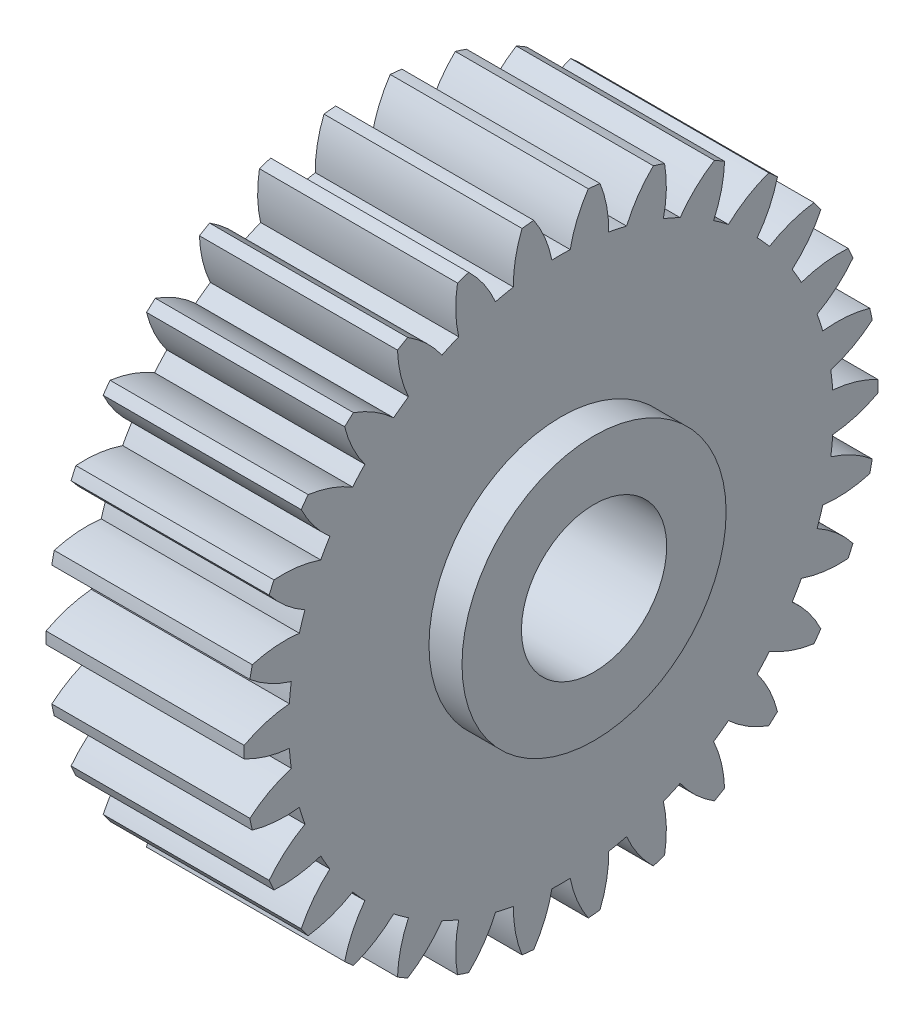
SolidWorks part; units mm, degrees
ref_plane "Plane1" through (0, 0, 0) normal (0, 0, 1) x (1, 0, 0)
ref_plane "Plane2" through (0, 0, 0) normal (0, 1, 0) x (1, 0, 0)
ref_plane "Plane3" through (0, 0, 0) normal (1, 0, 0) x (0, 0, -1)
other "Configuration Table"
sketch "HoldingSke" plane through (0, 0, 0) normal (0, 1, 0) x (1, 0, 0)
  line L0 (0, 0) -> (0.2887, -0.1667)
  line L1 (-15, 0) -> (100, 0) construction
  line L2 (0, 0) -> (-2.1039, 2.3779)
  line L3 (0, 0) -> (-11.863, 4.5341)
  line L4 (0, 0) -> (7.479, 4.318)
  line L5 (0, 0) -> (-37.4781, -13.9782)
  line L6 (0, 0) -> (-24.8689, -16.7791)
  line L7 (-2.1039, 2.3779) -> (6.5061, 41.4403)
  line L8 (-76.2, 54.61) -> (-72.9, 54.61)
  line L9 (-71.009, 38.7566) -> (-53.1078, 45.2721)
  line L10 (-76.2, 71.12) -> (104.1128, 71.12)
  line L11 (0, 0) -> (-30, 0)
  line L12 (-76.2, 101.6) -> (-76.093, 101.6)
  line L13 (24.9733, 27.94) -> (52.9518, 28.4284)
  line L14 (24.9733, 27.94) -> (24.9743, 27.94)
  line L15 (24.9733, 27.94) -> (100.4006, 29.5858)
  line L16 (-63.627, -3) -> (-12.827, -3)
  circle A0 centre (0, 0) radius 11
  circle A1 centre (0, 0) radius 20
  circle A2 centre (0, 0) radius 20
  circle A3 centre (0, 0) radius 11
  dimension "MHD" = 40
  dimension "Hub_dia" = 40
  dimension "Bore" = 22
  dimension "MBD" = 22
  dimension "Num_teeth" = 30
  dimension "Pitch" = 0.3333
  dimension "Overall_len" = 40
  dimension "Show_teeth" = 30
  dimension "Thickness" = 30
  dimension "OAL" = 40.0001
  dimension "T_dim" = 3.3
  dimension "Ap" = 20
  dimension "H" = 19.05
  dimension "Pitch_radius" = 180.3128
  dimension "Width" = 30
  dimension "Backlash" = 0.107
  dimension "Addendum_fac" = 1
  dimension "Dedendum_fac" = 1.25
  dimension "Clearance_fac" = 0.25
  dimension "Dedendum_add" = 0.001
  dimension "Module" = 3
sketch "BasProSke" plane through (0, 0, 0) normal (0, 1, 0) x (1, 0, 0)
  line L0 (-10, 0) -> (60, 0) construction
  line L1 (0, 0) -> (0, 48)
  line L2 (0, 0) -> (30, 0)
  line L3 (30, 0) -> (30, 48)
  line L4 (30, 48) -> (0, 48)
  dimension "Thickness" = 30
  dimension "Diameter" = 96
revolve "Base-Revolve" add sketch "BasProSke" angle 360 about L0
sketch "TooCutSke" plane through (0, 0, 0) normal (1, 0, 0) x (0, 0, -1)
  line L1 (0, 0) -> (0, 107) construction
  line L2 (0, 0) -> (-2.5423, 44.9281) construction
  line L3 (0, 0) -> (-9.3966, 89.403) construction
  line L4 (-2.5423, 44.9281) -> (-4.6983, 44.7015) construction
  arc A0 (1.3884, 41.2256) -> (-1.3884, 41.2256) centre (0, 0) ccw
  arc A1 (4.1466, 47.8461) -> (-4.1466, 47.8461) centre (0, 0) ccw
  circle A2 centre (0, 0) radius 45 construction
  circle A3 centre (0, 0) radius 42.2862 construction
  arc A4 (-1.3884, 41.2256) -> (-4.1466, 47.8461) centre (-19.05, 37.752) ccw
  arc A5 (4.1466, 47.8461) -> (1.3884, 41.2256) centre (19.05, 37.752) ccw
  dimension "Root_dia" = 82.498
  dimension "Overcut_dia" = 96.0508
  dimension "Pitch_dia" = 90
  dimension "Base_dia" = 84.5723
  dimension "Flank_rad" = 18
  dimension "Half_ang" = 6
  dimension "Half_CT" = 2.1679
extrude "ToothCut" cut sketch "TooCutSke" along normal through all
fillet "Breaks" [suppressed] radius 0.06
fillet "RootFillets" [suppressed] radius 0.751
pattern_circular "TeethCuts" count 30 every 12 about axis through (-10, 0, 0) along (1, 0, 0) of "ToothCut", "RootFillets", "Breaks"
sketch "HubNeaOneSke" plane through (0, 0, 0) normal (-1, 0, 0) x (0, 0, 1)
  circle A0 centre (0, 0) radius 20
  dimension "Diameter" = 40
extrude "HubNearOne" [suppressed] add sketch "HubNeaOneSke" along normal blind 10.0001
sketch "HubNeaBotSke" plane through (0, 0, 0) normal (-1, 0, 0) x (0, 0, 1)
  circle A0 centre (0, 0) radius 20
  dimension "Diameter" = 40
extrude "HubNearBoth" add sketch "HubNeaBotSke" along normal blind 5
ref_plane "FarPln" through (30, 0, 0) normal (1, 0, 0) x (0, 0, -1)
sketch "HubFarSke" plane through (30, 0, 0) normal (1, 0, 0) x (0, 0, -1)
  circle A0 centre (0, 0) radius 20
  dimension "Diameter" = 40
extrude "HubFar" add sketch "HubFarSke" along normal blind 5
sketch "BorSke" plane through (0, 0, 0) normal (1, 0, 0) x (0, 0, -1)
  circle A0 centre (0, 0) radius 11
  dimension "Diameter" = 22
extrude "Bore" cut sketch "BorSke" along normal mid plane 80.0001
sketch "KeySke" plane through (0, 0, 0) normal (1, 0, 0) x (0, 0, -1)
  line L0 (-4, 0) -> (-4, 14.3)
  line L1 (-4, 14.3) -> (4, 14.3)
  line L2 (4, 14.3) -> (4, 0)
  line L3 (0, 0) -> (0, 34) construction
  line L4 (-4, 0) -> (4, 0)
  dimension "Offset" = 14.3
  dimension "Width" = 8
extrude "Keyway" [suppressed] cut sketch "KeySke" along normal mid plane 80.0001
pattern_circular "Keyway2" [suppressed] count 2 every 90 about axis through (-10, 0, 0) along (1, 0, 0)
equation "' \"Module@HoldingSke\" = 6.35"
equation "' \"Num_teeth@HoldingSke\" = 12"
equation "' \"Ap@HoldingSke\" =  20"
equation "' \"Ap@HoldingSke\" = 20"
equation "' \"Width@HoldingSke\" = 0.5 * 25.4"
equation "' \"Hub_dia@HoldingSke\"= 1 * 25.4"
equation "' \"Hub_dia@HoldingSke\" = 1 * 25.4"
equation "' \"Overall_len@HoldingSke\" = 1.0 * 25.4"
equation "' \"Bore@HoldingSke\" = 0.75 * 25.4"
equation "' \"T_dim@HoldingSke\" = 0.1 * 25.4"
equation "' \"Width@KeySke\" = 0.25 * 25.4"
equation "' \"Show_teeth@HoldingSke\" = 13"
equation "' \"Backlash@HoldingSke\" = 0.009 * 25.4"
equation "' \"Addendum_fac@HoldingSke\" = 1.0"
equation "' \"Dedendum_fac@HoldingSke\" = 1.25"
equation "' \"Dedendum_add@HoldingSke\" = 0.00005 * 25.4"
equation "' \"Clearance_fac@HoldingSke\" = 0.25"
equation "\"Pitch@HoldingSke\" = 1 / \"Module@HoldingSke\""
equation "\"Overcut_dia@TooCutSke\" = (\"Num_teeth@HoldingSke\" + 2 * \"Addendum_fac@HoldingSke\") / \"Pitch@HoldingSke\" + 0.002 * 25.4"
equation "\"Pitch_dia@TooCutSke\" = \"Num_teeth@HoldingSke\" / \"Pitch@HoldingSke\""
equation "\"Base_dia@TooCutSke\" = \"Num_teeth@HoldingSke\" / \"Pitch@HoldingSke\" * cos((\"Ap@HoldingSke\"  * 3.14159265 / 180))"
equation "\"Root_dia@TooCutSke\" = (\"Num_teeth@HoldingSke\" + 2) / \"Pitch@HoldingSke\" - 2 * (\"Addendum_fac@HoldingSke\" + \"Dedendum_fac@HoldingSke\") / \"Pitch@HoldingSke\" - \"Dedendum_add@HoldingSke\" * 2"
equation "\"Half_ang@TooCutSke\" = 180 / \"Num_teeth@HoldingSke\""
equation "\"Half_CT@TooCutSke\" = \"Num_teeth@HoldingSke\" / \"Pitch@HoldingSke\" * sin((3.14159265 / 2 / \"Num_teeth@HoldingSke\")) / 2 - 7 * \"Backlash@HoldingSke\" / 4"
equation "\"Flank_rad@TooCutSke\" = \"Num_teeth@HoldingSke\" / \"Pitch@HoldingSke\" / 5"
equation "\"Radius@RootFillets\" = \"Clearance_fac@HoldingSke\" / \"Pitch@HoldingSke\" + \"Dedendum_add@HoldingSke\""
equation "\"Break_rad@Breaks\" = 0.02 / \"Pitch@HoldingSke\""
equation "\"Thickness@HoldingSke\" = \"Width@HoldingSke\""
equation "\"OAL@HoldingSke\" = \"Thickness@HoldingSke\""
equation "\"MHD@HoldingSke\" = (\"Num_teeth@HoldingSke\" + 2) / \"Pitch@HoldingSke\" - 2 * (\"Addendum_fac@HoldingSke\" + \"Dedendum_fac@HoldingSke\")  / \"Pitch@HoldingSke\" - \"Dedendum_add@HoldingSke\" * 2"
equation "\"MBD@HoldingSke\" = (\"Num_teeth@HoldingSke\" + 2) / \"Pitch@HoldingSke\" - 2 * (\"Addendum_fac@HoldingSke\" + \"Dedendum_fac@HoldingSke\")  / \"Pitch@HoldingSke\" - \"Dedendum_add@HoldingSke\" * 2 - 0.002 * 25.4"
equation "\"MHD@HoldingSke\" = ((sgn( \"MHD@HoldingSke\" - \"Hub_dia@HoldingSke\" )-1)*( \"MHD@HoldingSke\" - \"Hub_dia@HoldingSke\" ))/-2+ \"Hub_dia@HoldingSke\""
equation "\"MBD@HoldingSke\" = ((sgn( \"MBD@HoldingSke\" - \"Bore@HoldingSke\" )-1)*( \"MBD@HoldingSke\" - \"Bore@HoldingSke\" ))/-2+ \"Bore@HoldingSke\""
equation "\"OAL@HoldingSke\" = ((sgn( \"OAL@HoldingSke\" - \"Overall_len@HoldingSke\" )+1)*( \"OAL@HoldingSke\" - \"Overall_len@HoldingSke\" ))/2 + \"Overall_len@HoldingSke\" + 0.000002 * 25.4"
equation "\"Num_teeth@TeethCuts\" = int( \"Show_teeth@HoldingSke\" ) + 1"
equation "\"Num_teeth@TeethCuts\" = ((sgn( \"Num_teeth@TeethCuts\" - \"Num_teeth@HoldingSke\" )-1)*( \"Num_teeth@TeethCuts\" - \"Num_teeth@HoldingSke\" ))/-2+ \"Num_teeth@HoldingSke\""
equation "\"Num_teeth@TeethCuts\" = ((sgn( \"Num_teeth@TeethCuts\" - 2.0)+1)*( \"Num_teeth@TeethCuts\" - 2.0))/2 +2.0"
equation "\"Angle@TeethCuts\" = 360.0 / \"Num_teeth@HoldingSke\""
equation "\"Diameter@BasProSke\" = (\"Num_teeth@HoldingSke\" + 2 * \"Addendum_fac@HoldingSke\") / \"Pitch@HoldingSke\""
equation "\"Thickness@BasProSke\"  = \"Thickness@HoldingSke\""
equation "' \"Fillet_rad@BasProSke\" =  \"Thickness@HoldingSke\" * 0.05"
equation "' \"Fillet_rad@BasProSke\" = \"Thickness@HoldingSke\" * 0.05"
equation "\"MHD@HoldingSke\" = ((sgn( \"MHD@HoldingSke\" - \"Root_dia@TooCutSke\" )-1)*( \"MHD@HoldingSke\" - \"Root_dia@TooCutSke\" ))/-2+ \"Root_dia@TooCutSke\""
equation "\"Diameter@HubNeaOneSke\" = \"MHD@HoldingSke\""
equation "\"Length@HubNearOne\" = \"OAL@HoldingSke\" - \"Thickness@BasProSke\""
equation "\"Diameter@HubNeaBotSke\" = \"MHD@HoldingSke\""
equation "\"Length@HubNearBoth\" = ( \"OAL@HoldingSke\" - \"Thickness@BasProSke\" ) / 2.0"
equation "\"Thickness@FarPln\" = \"Thickness@BasProSke\""
equation "\"Diameter@HubFarSke\" = \"MHD@HoldingSke\""
equation "\"Length@HubFar\" = ( \"OAL@HoldingSke\" - \"Thickness@BasProSke\" ) / 2.0"
equation "\"Diameter@BorSke\" = \"MBD@HoldingSke\""
equation "\"D1@Bore\" = \"OAL@HoldingSke\" * 2.0"
equation "\"D1@Keyway\" = \"OAL@HoldingSke\" * 2.0"
equation "\"Offset@KeySke\" = \"T_dim@HoldingSke\" + \"MBD@HoldingSke\" / 2.0"
